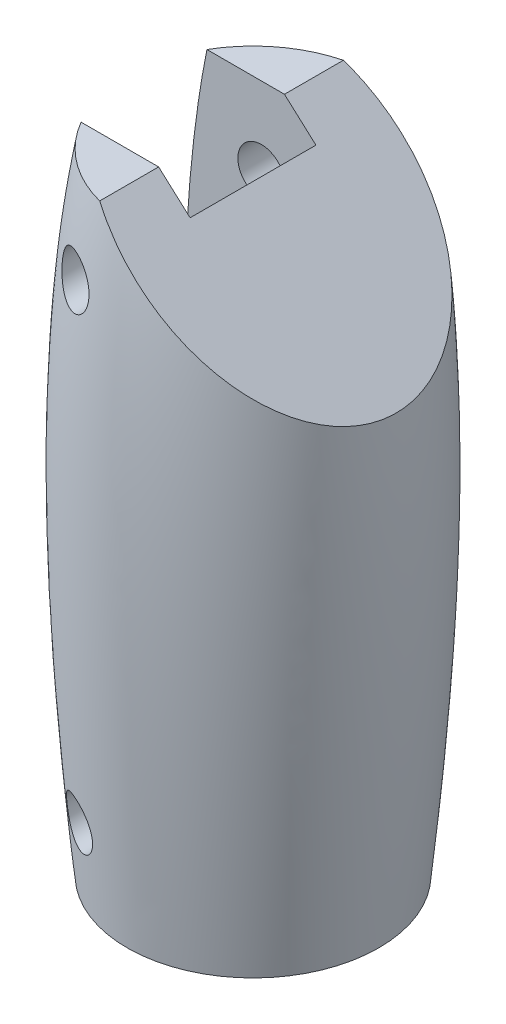
SolidWorks part; units mm, degrees
ref_plane "Front Plane" through (0, 0, 0) normal (0, 0, 1) x (1, 0, 0)
ref_plane "Top Plane" through (0, 0, 0) normal (0, 1, 0) x (1, 0, 0)
ref_plane "Right Plane" through (0, 0, 0) normal (1, 0, 0) x (0, 0, -1)
sketch "Sketch1" plane through (0, 0, 0) normal (1, 0, 0) x (0, 0, -1)
  line L0 (0, 20) -> (0, -20)
  line L1 (0, 20) -> (8, 20)
  line L2 (0, -20) -> (8, -20)
  line L3 (13.2094, -9.5442) -> (2.7906, 49.5442) construction
  spline S0 degree 2 poles (8, 20) (10.6047, 5.2279) (8, -20) knots 0 0 0 1 1 1
  point P3 (0, 0)
  dimension "D3" = 100
  dimension "D4" = 30
  dimension "D1" = 40
  dimension "D2" = 8
revolve "Revolve1" add sketch "Sketch1" angle 360 about L0
sketch "Sketch2" plane through (0, 0, 0) normal (1, 0, 0) x (0, 0, -1)
  line L0 (8, 20) -> (-8, 20) construction
  line L1 (-4, 7) -> (4, 7)
  line L2 (-4, 7) -> (-4, 20)
  line L3 (-4, 20) -> (4, 20)
  line L4 (4, 7) -> (4, 20)
  line L5 (-8, -20) -> (8, -20) construction
  line L6 (-4, -20) -> (4, -20)
  line L7 (-4, -20) -> (-4, -10)
  line L8 (-4, -10) -> (4, -10)
  line L9 (4, -20) -> (4, -10)
  point P12 (0, -10)
  point P14 (0, 7)
  dimension "D1" = 8
  dimension "D2" = 10
  dimension "D3" = 13
extrude "Cut-Extrude1" cut sketch "Sketch2" against normal through all
sketch "Sketch3" plane through (0, 0, 0) normal (0, 0, 1) x (1, 0, 0)
  line L0 (-3.4641, -20) -> (-3.4641, -15) construction
  line L2 (-3.4641, 20) -> (-3.4641, 15) construction
  line L3 (-6.9282, -20) -> (8, -20) construction
  line L6 (0, 20) -> (-6.9282, 20) construction
  circle A0 centre (-3.4641, 15) radius 1.5
  circle A1 centre (-3.4641, -15) radius 1.5
  point P0 (-3.4641, -20)
  point P12 (0, 0)
  point P13 (-3.4641, 20)
  dimension "D3" = 3
  dimension "D1" = 5
  dimension "D2" = 5
extrude "Cut-Extrude2" cut sketch "Sketch3" against normal through all and the other way through all
sketch "Sketch4" plane through (0, 0, 0) normal (0, 0, 1) x (1, 0, 0)
  line L0 (-2, 20) -> (9.1052, 10)
  line L1 (8, 20) -> (-6.9282, 20) construction
  line L2 (-2, 20) -> (8, 20)
  spline S0 degree 2 poles (-1099.3705, -2806.1136) (1341.9727, 2736.3374) (-1592.6223, -2511.1435) knots -14.088343 -14.088343 -14.088343 18.035788 18.035788 18.035788 only from (8, -20) to (8, 20) construction
  spline S1 degree 2 poles (9.1052, 10) (8.7956, 15.4878) (8, 20) knots 0.694545 0.694545 0.694545 1 1 1
  dimension "D1" = 10
  dimension "D2" = 10
extrude "Cut-Extrude3" cut sketch "Sketch4" against normal blind 10 and the other way blind 10
